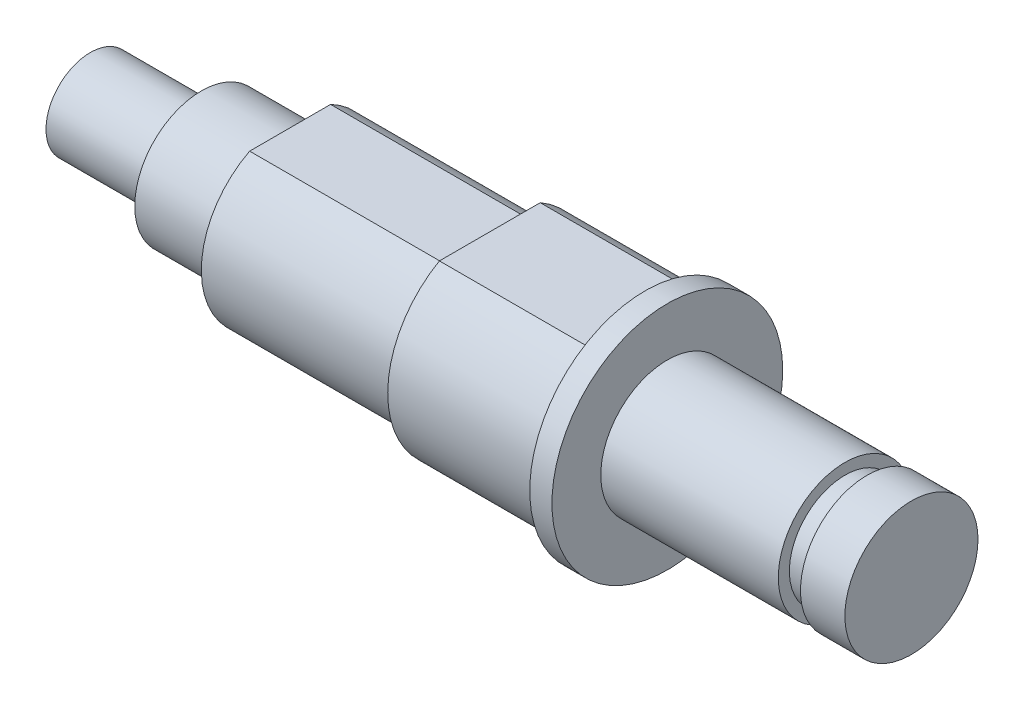
SolidWorks part; units mm, degrees
ref_plane "前视基准面" through (0, 0, 0) normal (0, 0, 1) x (1, 0, 0)
ref_plane "上视基准面" through (0, 0, 0) normal (0, 1, 0) x (1, 0, 0)
ref_plane "右视基准面" through (0, 0, 0) normal (1, 0, 0) x (0, 0, -1)
sketch "草图1" plane through (0, 0, 0) normal (1, 0, 0) x (0, 0, -1)
  circle A0 centre (0, 0) radius 1.5
extrude "凸台-拉伸1" add sketch "草图1" along normal blind 18.5
ref_plane "基准面1" through (9, 0, 0) normal (-1, 0, 0) x (0, 0, 1)
sketch "草图2" plane through (9, 0, 0) normal (-1, 0, 0) x (0, 0, 1)
  line L0 (-1.1358, 2) -> (1.1358, 2)
  arc A0 (-1.1358, 2) -> (1.1358, 2) centre (0, 0) ccw
  circle A1 centre (0, 0) radius 1.5
  dimension "D1" = 2
extrude "凸台-拉伸2" add sketch "草图2" against normal blind 3.5
sketch "草图3" plane through (12.5, 0, 0) normal (1, 0, 0) x (0, 0, -1)
  circle A0 centre (0, 0) radius 1.5
  circle A1 centre (0, 0) radius 2.6
extrude "凸台-拉伸3" add sketch "草图3" along normal blind 0.5
sketch "草图7" plane through (9, 0, 0) normal (-1, 0, 0) x (0, 0, 1)
  line L0 (-0.9119, 1.78) -> (0.9119, 1.78)
  circle A0 centre (0, 0) radius 1.5
  arc A1 (-0.9119, 1.78) -> (0.9119, 1.78) centre (0, 0) ccw
  dimension "D1" = 1.78
extrude "凸台-拉伸4" add sketch "草图7" along normal blind 4.5
sketch "草图4" plane through (18.5, 0, 0) normal (1, 0, 0) x (0, 0, -1)
  circle A0 centre (0, 0) radius 1.25
  circle A1 centre (0, 0) radius 1.5
extrude "切除-拉伸1" cut sketch "草图4" against normal blind 0.5 from offset 1 offset against normal yes
sketch "草图5" plane through (0, 0, 0) normal (-1, 0, 0) x (0, 0, 1)
  circle A0 centre (0, 0) radius 2
  circle A1 centre (0, 0) radius 1
extrude "切除-拉伸2" cut sketch "草图5" against normal blind 2.5
